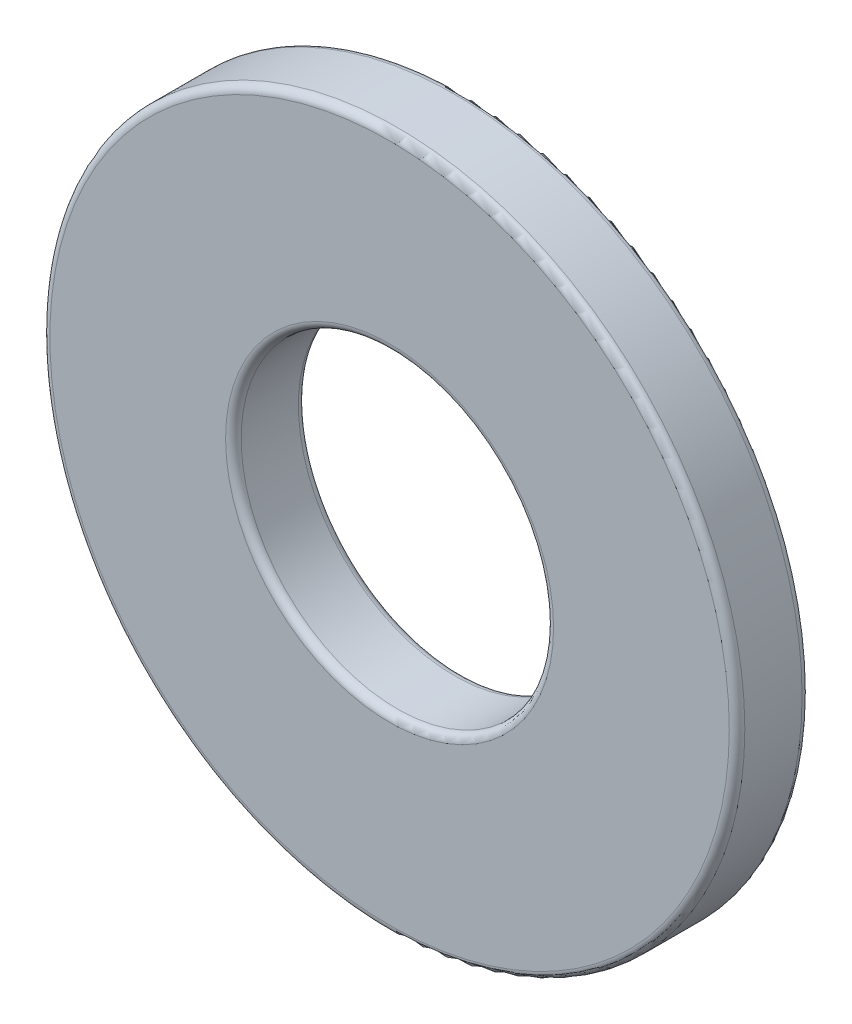
SolidWorks part; units mm, degrees
material "AISI 1020"
ref_plane "Front Plane" through (0, 0, 0) normal (1, 0, 0) x (0, 1, 0)
ref_plane "Top Plane" through (0, 0, 0) normal (0, 0, 1) x (0, 1, 0)
ref_plane "Right Plane" through (0, 0, 0) normal (0, 1, 0) x (-1, 0, 0)
sketch "Sketch1" plane through (0, 0, 0) normal (0, 0, 1) x (0, 1, 0)
  circle A0 centre (0, 0) radius 7.9375
  circle A1 centre (0, 0) radius 3.5687
  dimension "D1" = 7.1374
  dimension "D2" = 15.875
extrude "Boss-Extrude1" add sketch "Sketch1" along normal mid plane 1.6637
fillet "Fillet2" radius 0.1778 4 edges at (3.5687, 0, 0.8318) (7.9375, 0, 0.8318) (3.5687, 0, -0.8318) (7.9375, 0, -0.8318)
